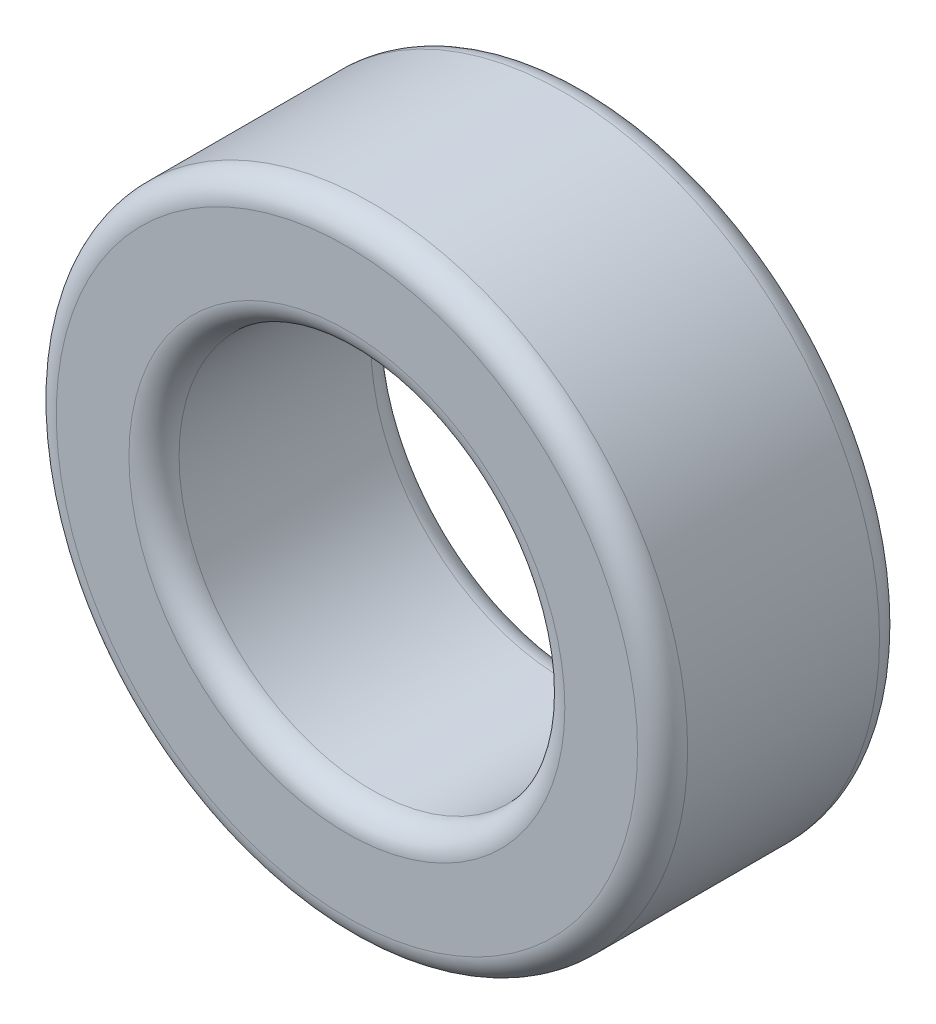
SolidWorks part; units mm, degrees
ref_plane "Спереди" through (0, 0, 0) normal (0, 0, 1) x (1, 0, 0)
ref_plane "Сверху" through (0, 0, 0) normal (0, 1, 0) x (1, 0, 0)
ref_plane "Справа" through (0, 0, 0) normal (1, 0, 0) x (0, 0, -1)
sketch "Эскиз1" plane through (0, 0, 0) normal (0, 0, 1) x (1, 0, 0)
  circle A0 centre (0, 0) radius 3.85
  circle A1 centre (0, 0) radius 6.3
  dimension "D1" = 12.6
  dimension "D2" = 7.7
extrude "Бобышка-Вытянуть1" add sketch "Эскиз1" along normal blind 4.83
fillet "Скругление1" radius 0.5 4 edges at (3.85, 0, 4.83) (6.3, 0, 4.83) (6.3, 0, 0) (3.85, 0, 0)
sketch "Эскиз5" plane through (0, 0, 0) normal (0, 0, -1) x (-1, 0, 0)
  line L0 (-3.5343, -0.394) -> (0, 0) construction
  circle A2 centre (-3.5343, -0.394) radius 0.3034
  circle A3 centre (0.0018, 0.0002) radius 3.5581 construction
  circle A4 centre (-3.389, 1.0776) radius 0.3034
  circle A5 centre (-2.6577, 2.3629) radius 0.3034
  circle A6 centre (-1.4668, 3.2396) radius 0.3034
  circle A7 centre (-0.0224, 3.5562) radius 0.3034
  circle A8 centre (1.426, 3.2578) radius 0.3034
  circle A9 centre (2.6278, 2.3961) radius 0.3034
  circle A10 centre (3.3752, 1.1202) radius 0.3034
  circle A11 centre (3.539, -0.3495) radius 0.3034
  circle A12 centre (3.0909, -1.7587) radius 0.3034
  circle A13 centre (2.1083, -2.8638) radius 0.3034
  circle A14 centre (0.7612, -3.4738) radius 0.3034
  circle A15 centre (-0.7175, -3.4831) radius 0.3034
  circle A16 centre (-2.0722, -2.8901) radius 0.3034
  circle A17 centre (-3.0685, -1.7974) radius 0.3034
  point P6 (0, 0)
  point P7 (0, 0)
  point P8 (0, 0)
  point P37 (0, 0)
  dimension "D1" = 15
  dimension "D2" = 1.4787
sketch "Эскиз7" plane through (0, 0, 4.83) normal (0, 0, 1) x (1, 0, 0)
  circle A0 centre (-2.6499, -2.3763) radius 0.3034
  circle A1 centre (-0.0018, 0.0002) radius 3.5581 construction
  circle A2 centre (-3.3886, -1.0906) radius 0.3034
  circle A3 centre (-2.1083, -2.8638) radius 0.3034 construction
  circle A4 centre (-3.0909, -1.7587) radius 0.3034 construction
  point P13 (-2.6499, -2.3763)
  dimension "D1" = 1.4828
